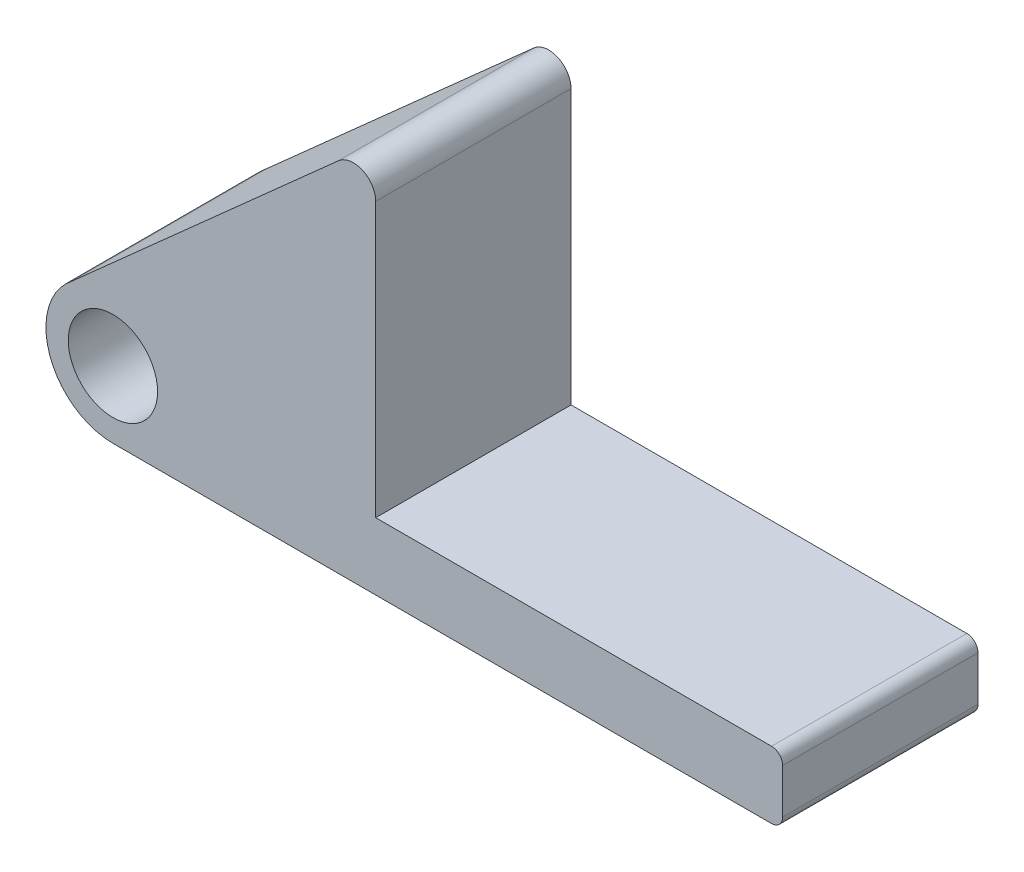
SolidWorks part; units mm, degrees
ref_plane "Plan de face" through (0, 0, 0) normal (0, 0, 1) x (1, 0, 0)
ref_plane "Plan de dessus" through (0, 0, 0) normal (0, 1, 0) x (1, 0, 0)
ref_plane "Plan de droite" through (0, 0, 0) normal (1, 0, 0) x (0, 0, -1)
sketch "Esquisse1" plane through (0, 0, 0) normal (0, 0, 1) x (1, 0, 0)
  line L0 (0, -6) -> (60, -6) construction
  line L1 (60, -6) -> (60, 0) construction
  line L2 (60, 0) -> (23.5434, 0) construction
  line L3 (23.5434, 0) -> (23.5434, 29) construction
  line L4 (23.5434, 29) -> (-3.6759, 4.7421) construction
  line L5 (-3.6759, 4.7421) -> (23.5434, 29)
  line L6 (23.5434, 29) -> (23.5434, 0)
  line L7 (23.5434, 0) -> (60, 0)
  line L8 (60, 0) -> (60, -6)
  line L9 (60, -6) -> (0, -6)
  circle A0 centre (0, 0) radius 6
  circle A1 centre (0, 0) radius 4
  dimension "D1" = 12
  dimension "D2" = 8
  dimension "D3" = 29
  dimension "D4" = 6
  dimension "D5" = 60
extrude "Boss.-Extru.1" add sketch "Esquisse1" against normal blind 17.5 contours A0 A1 | A0 L9 L8 L7 L6 L5
fillet "Congé2" radius 2 1 edges at (23.5434, 29, -8.75)
fillet "Congé3" radius 1 1 edges at (60, 0, -8.75)
fillet "Congé4" radius 1 1 edges at (60, -6, -8.75)
